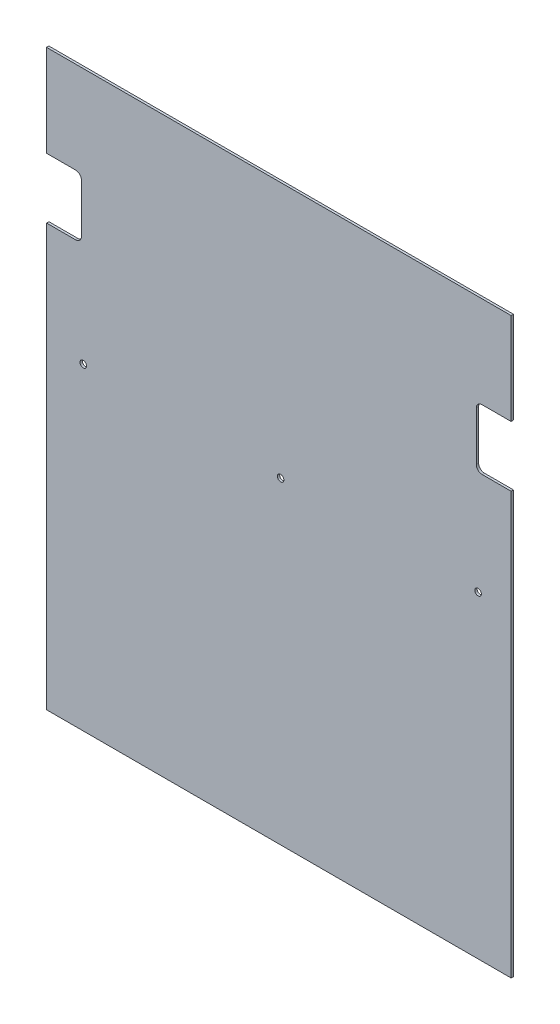
SolidWorks part; units mm, degrees
ref_plane "Front Plane" through (0, 0, 0) normal (0, 0, 1) x (1, 0, 0)
ref_plane "Top Plane" through (0, 0, 0) normal (0, 1, 0) x (1, 0, 0)
ref_plane "Right Plane" through (0, 0, 0) normal (1, 0, 0) x (0, 0, -1)
sketch "Sketch1" plane through (0, 0, 0) normal (0, 0, 1) x (1, 0, 0)
  line L0 (0, 0) -> (0, -494) construction
  line L1 (-200, 0) -> (200, 0)
  line L2 (-200, 0) -> (-200, -494)
  line L3 (-200, -494) -> (200, -494)
  line L4 (200, 0) -> (200, -494)
  dimension "D1" = 494
  dimension "D2" = 400
extrude "Boss-Extrude1" add sketch "Sketch1" along normal blind 2
sketch "Sketch5" plane through (0, 0, 2) normal (0, 0, 1) x (1, 0, 0)
  line L0 (0, 0) -> (0, -494) construction
  line L1 (-200, 0) -> (200, 0) construction
  line L2 (-200, -494) -> (200, -494) construction
  line L4 (-200, 0) -> (-200, -494) construction
  line L12 (-200, -106) -> (-200, -79)
  line L13 (-200, -79) -> (-170, -79)
  line L15 (-200, -106) -> (-170, -106) construction
  line L18 (-200, -106) -> (-200, -131)
  line L20 (-200, -131) -> (-170, -131)
  line L21 (-170, -131) -> (-170, -106)
  line L29 (-170, -106) -> (-170, -79)
  line L36 (200, -131) -> (170, -131)
  line L37 (200, -106) -> (200, -131)
  line L38 (200, -106) -> (200, -79)
  line L39 (200, -79) -> (170, -79)
  line L40 (170, -106) -> (170, -79)
  line L41 (170, -131) -> (170, -106)
  dimension "D1" = 106
  dimension "D2" = 25
  dimension "D3" = 30
  dimension "D6" = 27
extrude "Cut-Extrude3" cut sketch "Sketch5" against normal blind 10
fillet "Fillet1" radius 5 4 edges at (170, -79, 1) (170, -131, 1) (-170, -131, 1) (-170, -79, 1)
extrude "Cut-Extrude4" cut sketch "Sketch6" along normal blind 60
sketch "Sketch6" plane through (1.5445, -237.4582, 2) normal (0, 0, -1) x (-1, 0, 0)
  line L4 (200, 14.1784) -> (-200, 14.1784) construction
  line L5 (200, 19.8216) -> (-200, 19.8216) construction
  line L6 (-200, 476) -> (200, 476) construction
  line L7 (200, 484) -> (-200, 484) construction
  line L8 (0, 19.8216) -> (0, 14.1784) construction
  line L10 (-200, 248.5) -> (200, 248.5) construction
  line L11 (-170, 480) -> (170, 480) construction
  line L14 (0, 0) -> (0, 248.5) construction
  circle A0 centre (-170, 17) radius 2.8216
  circle A1 centre (0, 17) radius 2.8216
  circle A2 centre (170, 17) radius 2.8216
  circle A3 centre (170, 480) radius 2.8216
  circle A4 centre (0, 480) radius 2.8216
  circle A5 centre (-170, 480) radius 2.8216
